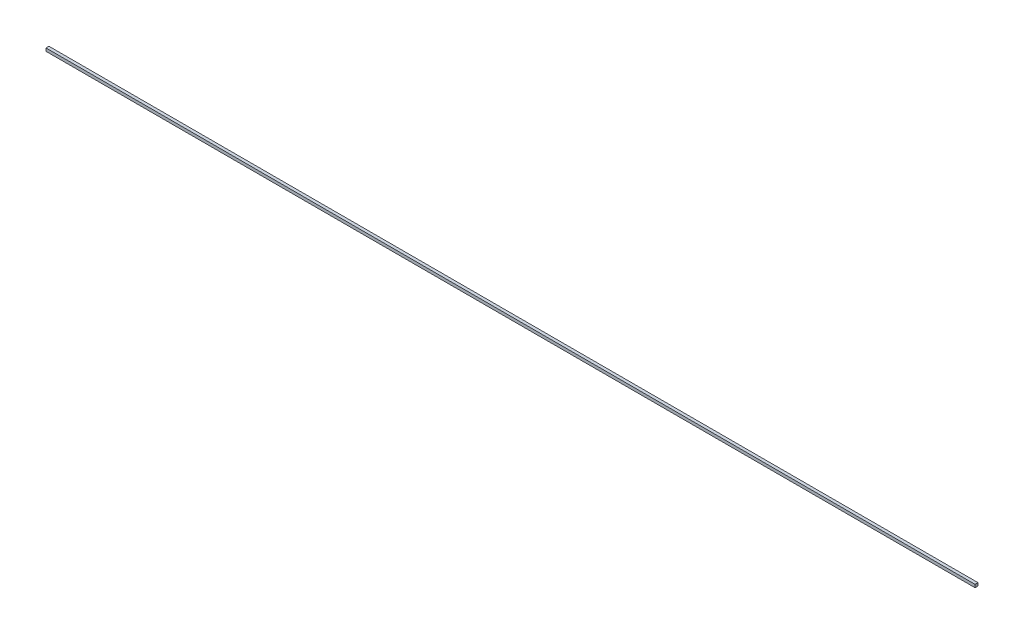
SolidWorks part; units mm, degrees
material "Balsa"
ref_plane "Front Plane" through (0, 0, 0) normal (0, 0, 1) x (1, 0, 0)
ref_plane "Top Plane" through (0, 0, 0) normal (0, 1, 0) x (1, 0, 0)
ref_plane "Right Plane" through (0, 0, 0) normal (1, 0, 0) x (0, 0, -1)
sketch "Sketch1" plane through (0, 0, 0) normal (1, 0, 0) x (0, 0, -1)
  line L1 (-1.5875, 1.5875) -> (1.5875, 1.5875)
  line L2 (-1.5875, 1.5875) -> (-1.5875, -1.5875)
  line L3 (-1.5875, -1.5875) -> (1.5875, -1.5875)
  line L4 (1.5875, 1.5875) -> (1.5875, -1.5875)
  line L5 (-1.5875, 1.5875) -> (1.5875, -1.5875) construction
  line L6 (-1.5875, -1.5875) -> (1.5875, 1.5875) construction
  point P0 (0, 0)
  dimension "D1" = 3.175
extrude "Boss-Extrude1" add sketch "Sketch1" along normal mid plane 1000
